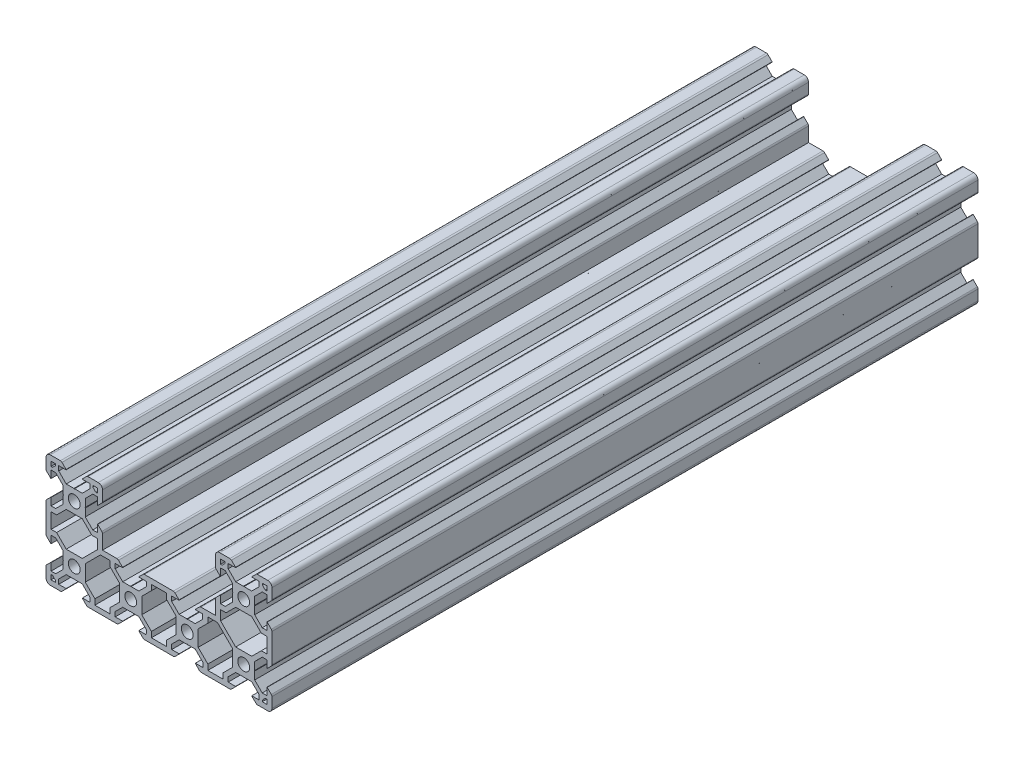
SolidWorks part; units mm, degrees
material "6061-T6 (SS)"
ref_plane "Front Plane" through (0, 0, 0) normal (0, 0, 1) x (1, 0, 0)
ref_plane "Top Plane" through (0, 0, 0) normal (0, 1, 0) x (1, 0, 0)
ref_plane "Right Plane" through (0, 0, 0) normal (1, 0, 0) x (0, 0, -1)
sketch "Sketch3" plane through (0, 0, 0) normal (0, 0, 1) x (1, 0, 0)
  line L5 (-8.2, 2.8825) -> (-8.2, 5.4959)
  line L6 (-4.8999, 10.0096) -> (-8.496, 10.0096)
  line L14 (-10, 4.8997) -> (-10, 8.5056)
  line L18 (-999.9992, 0.0096) -> (49000.0008, 0.0096) construction
  line L19 (0, -999.9929) -> (0, 49000.0071) construction
  line L20 (-0.1067, 3.9071) -> (-2.835, 3.9071)
  line L22 (-3.9, 0.0983) -> (-3.9, 2.8367)
  line L24 (-2.8827, 8.208) -> (-5.496, 8.208)
  line L25 (-6.57, 8.208) -> (-6.57, 7.668)
  line L26 (-8.2, 6.578) -> (-7.66, 6.578)
  line L44 (-5.496, 8.208) -> (-5.496, 6.566)
  line L46 (-6.56, 5.4959) -> (-8.2, 5.4959)
  line L58 (30, -1000.0108) -> (30, 48999.9892) construction
  line L65 (-6.56, 5.4959) -> (-3.9, 2.8367)
  line L66 (-5.496, 6.566) -> (-2.835, 3.9071)
  line L67 (-7.66, 6.578) -> (-6.57, 7.668)
  line L68 (-8.2, 6.578) -> (-8.2, 8.208)
  line L69 (-6.57, 8.208) -> (-8.2, 8.208)
  line L70 (-2.8827, 8.3196) -> (-2.8827, 8.208)
  line L71 (-8.31, 2.8825) -> (-8.2, 2.8825)
  line L72 (-4.3413, 9.7782) -> (-2.8827, 8.3196)
  line L73 (-8.31, 2.8825) -> (-9.7686, 4.3411)
  line L74 (-0.1067, 3.9071) -> (0, 3.8071)
  line L75 (-3.9, 0.0983) -> (-3.7992, 0.0096)
  line L76 (-8.2, -7.2977) -> (-6.2381, -7.2977)
  line L77 (-8.31, -17.115) -> (-9.7657, -15.6593)
  line L78 (0, -3.9016) -> (-2.835, -3.9016)
  line L79 (-3.7992, 0.0096) -> (-3.9, -0.1033)
  line L80 (-3.9, -0.1033) -> (-3.9, -2.8417)
  line L81 (-2.835, -3.9016) -> (-6.2381, -7.2977)
  line L82 (-3.9, -2.8417) -> (-6.56, -5.4962)
  line L83 (-8.2, -2.8829) -> (-8.2, -5.4962)
  line L84 (-8.2, -17.115) -> (-8.31, -17.115)
  line L85 (-6.56, -5.4962) -> (-8.2, -5.4962)
  line L86 (10, -9.9904) -> (15.1019, -9.9904)
  line L87 (-8.2, -2.8829) -> (-8.31, -2.8829)
  line L88 (-8.31, -2.8829) -> (-9.7657, -4.3385)
  line L89 (-1000, -19.9904) -> (49000, -19.9904) construction
  line L90 (-8.2, -7.2977) -> (-8.2, -12.6899)
  line L91 (-10, -4.9042) -> (-10, -15.0936)
  line L92 (-6.56, -14.5017) -> (-8.2, -14.5017)
  line L93 (-8.2, -17.115) -> (-8.2, -14.5017)
  line L94 (-3.9, -17.1683) -> (-6.56, -14.5017)
  line L95 (-2.8404, -16.0895) -> (-6.24, -12.6899)
  line L96 (-3.9, -19.9066) -> (-3.9, -17.1683)
  line L97 (-3.8052, -20.0014) -> (-3.9, -19.9066)
  line L98 (0, -16.0895) -> (-2.8404, -16.0895)
  line L99 (-8.2, -12.6899) -> (-6.24, -12.6899)
  line L100 (-3.9, -20.0962) -> (-3.8052, -20.0014)
  line L101 (-0.0887, -23.8929) -> (0, -23.7929)
  line L102 (-8.31, -22.8804) -> (-9.7686, -24.339)
  line L103 (-4.334, -29.759) -> (-2.8754, -28.3004)
  line L104 (-8.31, -22.8804) -> (-8.2, -22.8804)
  line L105 (-2.8754, -28.3004) -> (-2.8754, -28.1904)
  line L106 (-6.57, -28.1904) -> (-8.2, -28.1904)
  line L107 (-8.2, -26.5604) -> (-8.2, -28.1904)
  line L108 (-7.66, -26.5604) -> (-6.57, -27.6504)
  line L109 (-5.4887, -26.5517) -> (-2.8291, -23.8929)
  line L110 (-6.56, -25.4937) -> (-3.9, -22.8345)
  line L111 (-6.56, -25.4937) -> (-8.2, -25.4937)
  line L112 (-5.4887, -28.1904) -> (-5.4887, -26.5517)
  line L113 (-8.2, -26.5604) -> (-7.66, -26.5604)
  line L114 (-6.57, -28.1904) -> (-6.57, -27.6504)
  line L115 (-2.8754, -28.1904) -> (-5.4887, -28.1904)
  line L116 (-3.9, -20.0962) -> (-3.9, -22.8345)
  line L117 (-0.0887, -23.8929) -> (-2.8291, -23.8929)
  line L118 (-10, -24.8976) -> (-10, -28.4904)
  line L119 (-4.9072, -29.9904) -> (-8.5, -29.9904)
  line L120 (-8.2, -22.8804) -> (-8.2, -25.4937)
  line L121 (20, -1019.9807) -> (20, 48980.0193) construction
  line L122 (-972.545, -9.9904) -> (49027.455, -9.9904) construction
  line L123 (-8.2, 2.8825) -> (-8.2, -2.8829) construction
  line L124 (-8.2, -17.115) -> (-8.2, -22.8804) construction
  line L125 (-2.8754, -28.1904) -> (2.89, -28.1904) construction
  line L126 (17.11, -28.1904) -> (22.8754, -28.1904) construction
  line L127 (17.1233, -11.7895) -> (22.8887, -11.7904) construction
  line L128 (8.2, -2.8829) -> (8.2, 2.8825) construction
  line L129 (2.8827, 8.208) -> (-2.8827, 8.208) construction
  line L130 (57.1173, 8.208) -> (62.8827, 8.208) construction
  line L131 (51.8, -2.8829) -> (51.8, 2.8825) construction
  line L132 (42.8767, -11.7895) -> (37.1113, -11.7904) construction
  line L133 (22.8482, -16.0895) -> (20.1099, -16.0895)
  line L134 (42.89, -28.1904) -> (37.1246, -28.1904) construction
  line L135 (62.8754, -28.1904) -> (57.11, -28.1904) construction
  line L136 (68.2, -17.115) -> (68.2, -22.8804) construction
  line L137 (68.2, 2.8825) -> (68.2, -2.8829) construction
  line L138 (51.8, 2.8825) -> (51.8, 5.4959)
  line L139 (55.1001, 10.0096) -> (51.504, 10.0096)
  line L140 (50, 4.8997) -> (50, 8.5056)
  line L141 (59.8933, 3.9071) -> (57.165, 3.9071)
  line L142 (56.1, 0.0983) -> (56.1, 2.8367)
  line L143 (57.1173, 8.208) -> (54.504, 8.208)
  line L144 (53.43, 8.208) -> (53.43, 7.668)
  line L145 (27.3193, -13.7504) -> (23.9096, -17.16)
  line L146 (22.8482, -16.0895) -> (25.5078, -13.4299)
  line L147 (51.8, 6.578) -> (52.34, 6.578)
  line L148 (54.504, 8.208) -> (54.504, 6.566)
  line L149 (53.44, 5.4959) -> (51.8, 5.4959)
  line L150 (53.44, 5.4959) -> (56.1, 2.8367)
  line L151 (54.504, 6.566) -> (57.165, 3.9071)
  line L152 (2.89, -28.1904) -> (5.5033, -28.1904)
  line L153 (22.8887, -11.7904) -> (22.8887, -11.6804)
  line L154 (5.5033, -26.5513) -> (5.5033, -28.1904)
  line L155 (24.3444, -10.2247) -> (22.8887, -11.6804)
  line L156 (7.3096, -26.2431) -> (7.3096, -28.1904)
  line L157 (2.89, -28.1904) -> (2.89, -28.3004)
  line L158 (2.89, -28.3004) -> (4.3457, -29.7561)
  line L159 (7.3096, -28.1904) -> (12.7, -28.1904)
  line L160 (16.1096, -17.16) -> (16.1096, -22.8307)
  line L161 (17.1705, -23.8929) -> (19.9105, -23.8929)
  line L162 (12.7, -26.2404) -> (16.1096, -22.8307)
  line L163 (17.1705, -23.8929) -> (14.4967, -26.5525)
  line L164 (17.11, -28.1904) -> (17.11, -28.3004)
  line L165 (4.9114, -29.9904) -> (15.0886, -29.9904)
  line L166 (15.6543, -29.7561) -> (17.11, -28.3004)
  line L167 (52.34, 6.578) -> (53.43, 7.668)
  line L168 (19.9105, -23.8929) -> (20.0109, -23.7929)
  line L169 (14.4967, -28.1904) -> (14.4967, -26.5525)
  line L170 (12.7, -28.1904) -> (12.7, -26.2404)
  line L171 (51.8, 6.578) -> (51.8, 8.208)
  line L172 (14.4967, -28.1904) -> (17.11, -28.1904)
  line L173 (20.1108, -23.8929) -> (20.0109, -23.7929)
  line L174 (25.502, -11.7904) -> (25.5078, -13.4299)
  line L175 (32.6807, -28.1904) -> (27.3193, -28.1904)
  line L176 (35.1033, -29.9904) -> (24.8967, -29.9904)
  line L177 (25.4887, -28.1904) -> (22.8754, -28.1904)
  line L178 (27.3193, -28.1904) -> (27.3193, -26.2304)
  line L179 (25.4887, -28.1904) -> (25.5159, -26.5596)
  line L180 (53.43, 8.208) -> (51.8, 8.208)
  line L181 (24.3311, -29.7561) -> (22.8754, -28.3004)
  line L182 (22.8754, -28.1904) -> (22.8754, -28.3004)
  line L183 (22.8492, -23.8929) -> (25.5159, -26.5596)
  line L184 (27.3193, -26.2304) -> (23.9096, -22.8207)
  line L185 (22.8492, -23.8929) -> (20.1108, -23.8929)
  line L186 (23.9096, -17.16) -> (23.9096, -22.8207)
  line L187 (27.3193, -11.7904) -> (27.3193, -13.7504)
  line L188 (25.502, -11.7904) -> (22.8887, -11.7904)
  line L189 (35.0899, -9.9904) -> (24.9101, -9.9904)
  line L190 (32.6807, -11.7904) -> (27.3193, -11.7904)
  line L191 (20.1099, -16.0895) -> (20.0097, -16.1897)
  line L192 (14.51, -11.7895) -> (17.1233, -11.7895)
  line L193 (12.7, -11.7987) -> (12.7, -13.7504)
  line L194 (14.51, -11.7895) -> (14.51, -13.4299)
  line L195 (19.9096, -16.0895) -> (20.0097, -16.1897)
  line L196 (0.0887, -23.8929) -> (2.8291, -23.8929)
  line L197 (15.6676, -10.2297) -> (17.1233, -11.6854)
  line L198 (57.1173, 8.3196) -> (57.1173, 8.208)
  line L199 (17.1233, -11.7895) -> (17.1233, -11.6854)
  line L200 (17.1696, -16.0895) -> (14.51, -13.4299)
  line L201 (12.7, -13.7504) -> (16.1096, -17.16)
  line L202 (17.1696, -16.0895) -> (19.9096, -16.0895)
  line L203 (51.69, 2.8825) -> (51.8, 2.8825)
  line L204 (9.2696, -11.7987) -> (12.7, -11.7987)
  line L205 (55.6587, 9.7782) -> (57.1173, 8.3196)
  line L206 (51.69, 2.8825) -> (50.2314, 4.3411)
  line L207 (59.8933, 3.9071) -> (60, 3.8071)
  line L208 (56.1, 0.0983) -> (56.2008, 0.0096)
  line L209 (51.8, -7.2977) -> (53.7619, -7.2977)
  line L210 (2.84, -16.0895) -> (8.2, -10.7295)
  line L211 (60, -3.9016) -> (57.165, -3.9016)
  line L212 (56.2008, 0.0096) -> (56.1, -0.1033)
  line L213 (56.1, -0.1033) -> (56.1, -2.8417)
  line L214 (57.165, -3.9016) -> (53.7619, -7.2977)
  line L215 (56.1, -2.8417) -> (53.44, -5.4962)
  line L216 (51.8, -2.8829) -> (51.8, -5.4962)
  line L217 (53.44, -5.4962) -> (51.8, -5.4962)
  line L218 (51.8, -2.8829) -> (51.69, -2.8829)
  line L219 (51.69, -2.8829) -> (50.2343, -4.3385)
  line L220 (51.8, -7.2977) -> (51.8, -10.7295)
  line L221 (50, -4.9042) -> (50, -9.9904)
  line L222 (56.1, -17.1683) -> (50.7304, -11.7987)
  line L223 (56.1, -22.8345) -> (56.1, -17.1683)
  line L224 (60, -16.0895) -> (57.16, -16.0895)
  line L225 (59.9113, -23.8929) -> (60, -23.7929)
  line L226 (54.4967, -26.5513) -> (57.1709, -23.8929)
  line L227 (52.6904, -26.2431) -> (56.1, -22.8345)
  line L228 (57.16, -16.0895) -> (51.8, -10.7295)
  line L229 (50.7304, -11.7987) -> (47.3, -11.7987)
  line L230 (42.8304, -16.0895) -> (40.0904, -16.0895)
  line L231 (47.3, -13.7504) -> (43.8904, -17.16)
  line L232 (42.8304, -16.0895) -> (45.49, -13.4299)
  line L233 (42.8767, -11.7895) -> (42.8767, -11.6854)
  line L234 (44.3324, -10.2297) -> (42.8767, -11.6854)
  line L235 (59.9113, -23.8929) -> (57.1709, -23.8929)
  line L236 (40.0904, -16.0895) -> (39.9903, -16.1897)
  line L237 (45.49, -11.7895) -> (45.49, -13.4299)
  line L238 (47.3, -11.7987) -> (47.3, -13.7504)
  line L239 (45.49, -11.7895) -> (42.8767, -11.7895)
  line L240 (39.8901, -16.0895) -> (39.9903, -16.1897)
  line L241 (34.498, -11.7904) -> (37.1113, -11.7904)
  line L242 (32.6807, -11.7904) -> (32.6807, -13.7504)
  line L243 (36.0904, -17.16) -> (36.0904, -22.8207)
  line L244 (37.1508, -23.8929) -> (39.8892, -23.8929)
  line L245 (32.6807, -26.2304) -> (36.0904, -22.8207)
  line L246 (37.1508, -23.8929) -> (34.4841, -26.5596)
  line L247 (37.1246, -28.1904) -> (37.1246, -28.3004)
  line L248 (35.6689, -29.7561) -> (37.1246, -28.3004)
  line L249 (34.5113, -28.1904) -> (34.4841, -26.5596)
  line L250 (32.6807, -28.1904) -> (32.6807, -26.2304)
  line L251 (34.5113, -28.1904) -> (37.1246, -28.1904)
  line L252 (34.498, -11.7904) -> (34.4922, -13.4299)
  line L253 (39.8892, -23.8929) -> (39.9891, -23.7929)
  line L254 (45.5033, -28.1904) -> (42.89, -28.1904)
  line L255 (47.3, -28.1904) -> (47.3, -26.2404)
  line L256 (45.5033, -28.1904) -> (45.5033, -26.5525)
  line L257 (40.0895, -23.8929) -> (39.9891, -23.7929)
  line L258 (44.3457, -29.7561) -> (42.89, -28.3004)
  line L259 (55.0886, -29.9904) -> (44.9114, -29.9904)
  line L260 (42.89, -28.1904) -> (42.89, -28.3004)
  line L261 (42.8295, -23.8929) -> (45.5033, -26.5525)
  line L262 (47.3, -26.2404) -> (43.8904, -22.8307)
  line L263 (42.8295, -23.8929) -> (40.0895, -23.8929)
  line L264 (43.8904, -17.16) -> (43.8904, -22.8307)
  line L265 (52.6904, -28.1904) -> (47.3, -28.1904)
  line L266 (57.11, -28.3004) -> (55.6543, -29.7561)
  line L267 (57.11, -28.1904) -> (57.11, -28.3004)
  line L268 (52.6904, -26.2431) -> (52.6904, -28.1904)
  line L269 (35.6556, -10.2247) -> (37.1113, -11.6804)
  line L270 (54.4967, -26.5513) -> (54.4967, -28.1904)
  line L271 (37.1113, -11.7904) -> (37.1113, -11.6804)
  line L272 (57.11, -28.1904) -> (54.4967, -28.1904)
  line L273 (37.1518, -16.0895) -> (34.4922, -13.4299)
  line L274 (32.6807, -13.7504) -> (36.0904, -17.16)
  line L275 (37.1518, -16.0895) -> (39.8901, -16.0895)
  line L276 (68.2, -22.8804) -> (68.2, -25.4937)
  line L277 (64.9072, -29.9904) -> (68.5, -29.9904)
  line L278 (70, -24.8976) -> (70, -28.4904)
  line L279 (60.0887, -23.8929) -> (62.8291, -23.8929)
  line L280 (63.9, -20.0962) -> (63.9, -22.8345)
  line L281 (62.8754, -28.1904) -> (65.4887, -28.1904)
  line L282 (66.57, -28.1904) -> (66.57, -27.6504)
  line L283 (68.2, -26.5604) -> (67.66, -26.5604)
  line L284 (65.4887, -28.1904) -> (65.4887, -26.5517)
  line L285 (66.56, -25.4937) -> (68.2, -25.4937)
  line L286 (66.56, -25.4937) -> (63.9, -22.8345)
  line L287 (65.4887, -26.5517) -> (62.8291, -23.8929)
  line L288 (67.66, -26.5604) -> (66.57, -27.6504)
  line L289 (68.2, -26.5604) -> (68.2, -28.1904)
  line L290 (66.57, -28.1904) -> (68.2, -28.1904)
  line L291 (62.8754, -28.3004) -> (62.8754, -28.1904)
  line L292 (68.31, -22.8804) -> (68.2, -22.8804)
  line L293 (64.334, -29.759) -> (62.8754, -28.3004)
  line L294 (68.31, -22.8804) -> (69.7686, -24.339)
  line L295 (60.0887, -23.8929) -> (60, -23.7929)
  line L296 (63.9, -20.0962) -> (63.8052, -20.0014)
  line L297 (68.2, -12.6899) -> (66.24, -12.6899)
  line L298 (60, -16.0895) -> (62.8404, -16.0895)
  line L299 (63.8052, -20.0014) -> (63.9, -19.9066)
  line L300 (63.9, -19.9066) -> (63.9, -17.1683)
  line L301 (62.8404, -16.0895) -> (66.24, -12.6899)
  line L302 (63.9, -17.1683) -> (66.56, -14.5017)
  line L303 (68.2, -17.115) -> (68.2, -14.5017)
  line L304 (66.56, -14.5017) -> (68.2, -14.5017)
  line L305 (70, -4.9042) -> (70, -15.0936)
  line L306 (68.2, -7.2977) -> (68.2, -12.6899)
  line L307 (68.31, -2.8829) -> (69.7657, -4.3385)
  line L308 (68.2, -2.8829) -> (68.31, -2.8829)
  line L309 (50, -9.9904) -> (44.8981, -9.9904)
  line L310 (66.56, -5.4962) -> (68.2, -5.4962)
  line L311 (68.2, -17.115) -> (68.31, -17.115)
  line L312 (68.2, -2.8829) -> (68.2, -5.4962)
  line L313 (63.9, -2.8417) -> (66.56, -5.4962)
  line L314 (62.835, -3.9016) -> (66.2381, -7.2977)
  line L315 (63.9, -0.1033) -> (63.9, -2.8417)
  line L316 (63.7992, 0.0096) -> (63.9, -0.1033)
  line L317 (60, -3.9016) -> (62.835, -3.9016)
  line L318 (68.31, -17.115) -> (69.7657, -15.6593)
  line L319 (68.2, -7.2977) -> (66.2381, -7.2977)
  line L320 (63.9, 0.0983) -> (63.7992, 0.0096)
  line L321 (60.1067, 3.9071) -> (60, 3.8071)
  line L322 (68.31, 2.8825) -> (69.7686, 4.3411)
  line L323 (64.3413, 9.7782) -> (62.8827, 8.3196)
  line L324 (68.31, 2.8825) -> (68.2, 2.8825)
  line L325 (62.8827, 8.3196) -> (62.8827, 8.208)
  line L326 (66.57, 8.208) -> (68.2, 8.208)
  line L327 (68.2, 6.578) -> (68.2, 8.208)
  line L328 (67.66, 6.578) -> (66.57, 7.668)
  line L329 (65.496, 6.566) -> (62.835, 3.9071)
  line L330 (66.56, 5.4959) -> (63.9, 2.8367)
  line L331 (66.56, 5.4959) -> (68.2, 5.4959)
  line L332 (65.496, 8.208) -> (65.496, 6.566)
  line L333 (68.2, 6.578) -> (67.66, 6.578)
  line L334 (66.57, 8.208) -> (66.57, 7.668)
  line L335 (62.8827, 8.208) -> (65.496, 8.208)
  line L336 (63.9, 0.0983) -> (63.9, 2.8367)
  line L337 (60.1067, 3.9071) -> (62.835, 3.9071)
  line L338 (70, 4.8997) -> (70, 8.5056)
  line L339 (64.8999, 10.0096) -> (68.496, 10.0096)
  line L340 (68.2, 2.8825) -> (68.2, 5.4959)
  line L347 (7.3096, -26.2431) -> (3.9, -22.8345)
  line L348 (5.5033, -26.5513) -> (2.8291, -23.8929)
  line L356 (0.0887, -23.8929) -> (0, -23.7929)
  line L359 (0, -16.0895) -> (2.84, -16.0895)
  line L361 (3.9, -22.8345) -> (3.9, -17.1683)
  line L363 (3.9, -17.1683) -> (9.2696, -11.7987)
  line L366 (10, -4.9042) -> (10, -9.9904)
  line L367 (8.2, -7.2977) -> (8.2, -10.7295)
  line L369 (8.31, -2.8829) -> (9.7657, -4.3385)
  line L370 (8.2, -2.8829) -> (8.31, -2.8829)
  line L372 (6.56, -5.4962) -> (8.2, -5.4962)
  line L374 (8.2, -2.8829) -> (8.2, -5.4962)
  line L375 (3.9, -2.8417) -> (6.56, -5.4962)
  line L376 (2.835, -3.9016) -> (6.2381, -7.2977)
  line L377 (3.9, -0.1033) -> (3.9, -2.8417)
  line L378 (3.7992, 0.0096) -> (3.9, -0.1033)
  line L379 (0, -3.9016) -> (2.835, -3.9016)
  line L381 (8.2, -7.2977) -> (6.2381, -7.2977)
  line L382 (3.9, 0.0983) -> (3.7992, 0.0096)
  line L383 (0.1067, 3.9071) -> (0, 3.8071)
  line L384 (8.31, 2.8825) -> (9.7686, 4.3411)
  line L385 (4.3413, 9.7782) -> (2.8827, 8.3196)
  line L386 (8.31, 2.8825) -> (8.2, 2.8825)
  line L387 (2.8827, 8.3196) -> (2.8827, 8.208)
  line L388 (6.57, 8.208) -> (8.2, 8.208)
  line L389 (8.2, 6.578) -> (8.2, 8.208)
  line L390 (7.66, 6.578) -> (6.57, 7.668)
  line L391 (5.496, 6.566) -> (2.835, 3.9071)
  line L392 (6.56, 5.4959) -> (3.9, 2.8367)
  line L393 (6.56, 5.4959) -> (8.2, 5.4959)
  line L394 (5.496, 8.208) -> (5.496, 6.566)
  line L395 (8.2, 6.578) -> (7.66, 6.578)
  line L396 (6.57, 8.208) -> (6.57, 7.668)
  line L397 (2.8827, 8.208) -> (5.496, 8.208)
  line L398 (3.9, 0.0983) -> (3.9, 2.8367)
  line L399 (0.1067, 3.9071) -> (2.835, 3.9071)
  line L400 (10, 4.8997) -> (10, 8.5056)
  line L401 (4.8999, 10.0096) -> (8.496, 10.0096)
  line L402 (8.2, 2.8825) -> (8.2, 5.4959)
  arc A6 (-10, 8.5056) -> (-8.496, 10.0096) centre (-8.496, 8.5056) cw
  arc A7 (-9.7686, 4.3411) -> (-10, 4.8997) centre (-9.21, 4.8997) cw
  arc A8 (-4.3413, 9.7782) -> (-4.8999, 10.0096) centre (-4.8999, 9.2196) ccw
  arc A9 (-9.7657, -4.3385) -> (-10, -4.9042) centre (-9.2, -4.9042) ccw
  circle A10 centre (0, 0.0096) radius 2.1
  circle A11 centre (0, -19.9904) radius 2.1
  arc A12 (-9.7657, -15.6593) -> (-10, -15.0936) centre (-9.2, -15.0936) cw
  arc A13 (-4.334, -29.759) -> (-4.9072, -29.9904) centre (-4.8927, -29.2005) cw
  arc A14 (-9.7686, -24.339) -> (-10, -24.8976) centre (-9.21, -24.8976) ccw
  arc A15 (-10, -28.4904) -> (-8.5, -29.9904) centre (-8.5, -28.4904) ccw
  circle A16 centre (20, -19.9904) radius 2.1
  arc A17 (50, 8.5056) -> (51.504, 10.0096) centre (51.504, 8.5056) cw
  arc A18 (50.2314, 4.3411) -> (50, 4.8997) centre (50.79, 4.8997) cw
  arc A19 (55.6587, 9.7782) -> (55.1001, 10.0096) centre (55.1001, 9.2196) ccw
  arc A20 (15.6543, -29.7561) -> (15.0886, -29.9904) centre (15.0886, -29.1904) cw
  arc A21 (4.3457, -29.7561) -> (4.9114, -29.9904) centre (4.9114, -29.1904) ccw
  arc A22 (50.2343, -4.3385) -> (50, -4.9042) centre (50.8, -4.9042) ccw
  arc A23 (24.3311, -29.7561) -> (24.8967, -29.9904) centre (24.8967, -29.1904) ccw
  arc A24 (24.3444, -10.2247) -> (24.9101, -9.9904) centre (24.9101, -10.7904) cw
  arc A25 (44.3324, -10.2297) -> (44.8981, -9.9904) centre (44.903, -10.7903) cw
  arc A26 (35.6556, -10.2247) -> (35.0899, -9.9904) centre (35.0899, -10.7904) ccw
  arc A27 (15.6676, -10.2297) -> (15.1019, -9.9904) centre (15.097, -10.7903) ccw
  arc A28 (35.6689, -29.7561) -> (35.1033, -29.9904) centre (35.1033, -29.1904) cw
  arc A29 (55.6543, -29.7561) -> (55.0886, -29.9904) centre (55.0886, -29.1904) cw
  arc A30 (44.3457, -29.7561) -> (44.9114, -29.9904) centre (44.9114, -29.1904) ccw
  circle A31 centre (40, -19.9904) radius 2.1
  arc A32 (70, -28.4904) -> (68.5, -29.9904) centre (68.5, -28.4904) cw
  arc A33 (69.7686, -24.339) -> (70, -24.8976) centre (69.21, -24.8976) cw
  arc A34 (64.334, -29.759) -> (64.9072, -29.9904) centre (64.8927, -29.2005) ccw
  arc A35 (69.7657, -15.6593) -> (70, -15.0936) centre (69.2, -15.0936) ccw
  circle A36 centre (60, -19.9904) radius 2.1
  circle A37 centre (60, 0.0096) radius 2.1
  arc A38 (69.7657, -4.3385) -> (70, -4.9042) centre (69.2, -4.9042) cw
  arc A39 (64.3413, 9.7782) -> (64.8999, 10.0096) centre (64.8999, 9.2196) cw
  arc A40 (69.7686, 4.3411) -> (70, 4.8997) centre (69.21, 4.8997) ccw
  arc A41 (70, 8.5056) -> (68.496, 10.0096) centre (68.496, 8.5056) ccw
  arc A52 (9.7657, -4.3385) -> (10, -4.9042) centre (9.2, -4.9042) cw
  arc A53 (4.3413, 9.7782) -> (4.8999, 10.0096) centre (4.8999, 9.2196) cw
  arc A54 (9.7686, 4.3411) -> (10, 4.8997) centre (9.21, 4.8997) ccw
  arc A55 (10, 8.5056) -> (8.496, 10.0096) centre (8.496, 8.5056) ccw
  point P68 (-10, -9.9989)
  point P69 (-8.2, -9.9938)
  point P107 (30, -9.9904)
  point P109 (30, -28.1904)
  point P116 (30, -9.9904)
  point P171 (30, -28.1904)
  point P215 (30, -9.9904)
  point P295 (30, -11.7904)
  point P306 (30, -29.9904)
  point P346 (30, -11.7904)
  point P360 (30, -29.9904)
  point P371 (30, -29.9904)
  point P372 (30, -11.7904)
  point P373 (30, -28.1904)
  point P374 (68.2, -9.9938)
  point P375 (70, -9.9989)
  dimension "D3" = 10
  dimension "D15" = 20
  dimension "D7" = 4.2
  dimension "D12" = 20
  dimension "D10" = 10
  dimension "D4" = 10
  dimension "D9" = 20
  dimension "D16" = 20
  dimension "D1" = 30
  dimension "D2" = 40
  dimension "D5" = 20
  dimension "D6" = 20
  dimension "D8" = 20
  dimension "D11" = 10
  dimension "D13" = 80
  dimension "D14" = 40
extrude "Boss-Extrude3" add sketch "Sketch3" along normal blind 250
